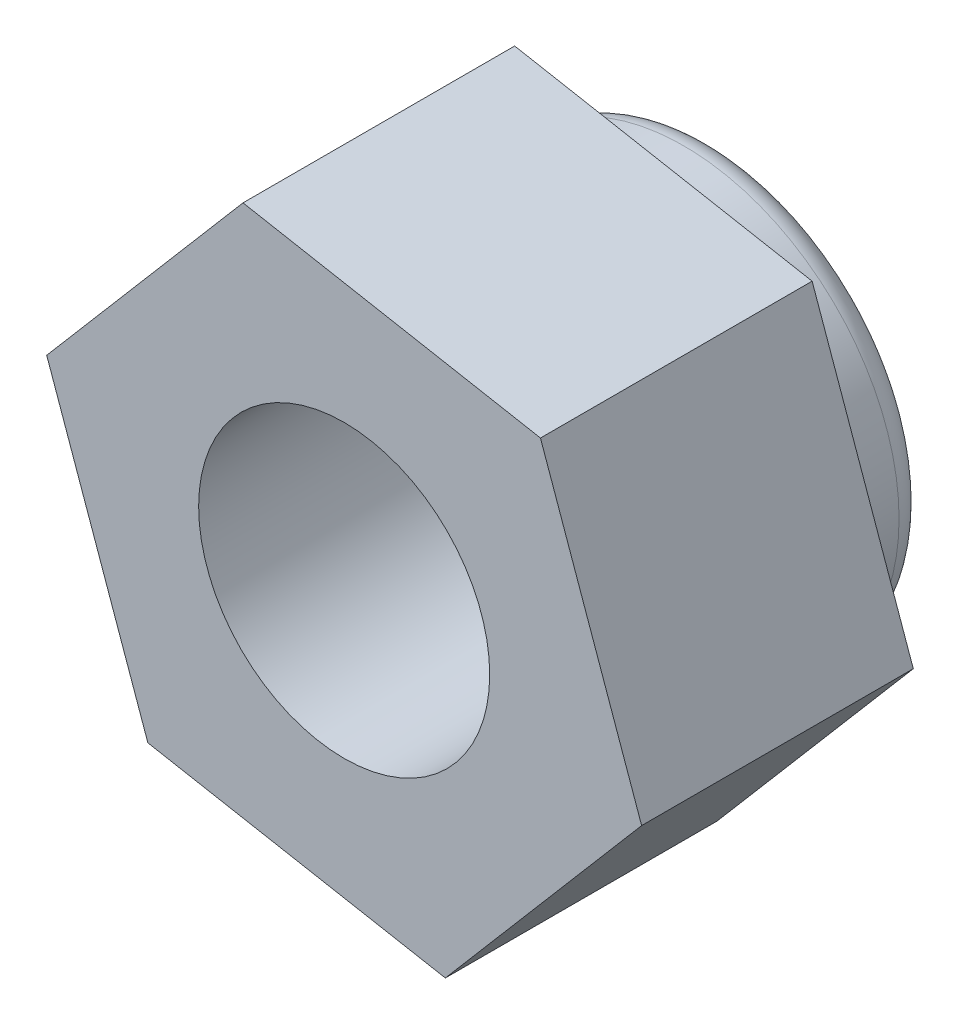
SolidWorks part; units mm, degrees
ref_plane "前视基准面" through (0, 0, 0) normal (0, 0, 1) x (1, 0, 0)
ref_plane "上视基准面" through (0, 0, 0) normal (0, 1, 0) x (1, 0, 0)
ref_plane "右视基准面" through (0, 0, 0) normal (1, 0, 0) x (0, 0, -1)
sketch "草图1" plane through (0, 0, 0) normal (0, 0, 1) x (1, 0, 0)
  line L1 (-1.0427, 2.9382) -> (-3.0659, 0.5661)
  line L2 (-3.0659, 0.5661) -> (-2.0232, -2.3721)
  line L3 (-2.0232, -2.3721) -> (1.0427, -2.9382)
  line L4 (1.0427, -2.9382) -> (3.0659, -0.5661)
  line L5 (3.0659, -0.5661) -> (2.0232, 2.3721)
  line L6 (2.0232, 2.3721) -> (-1.0427, 2.9382)
  circle A0 centre (0, 0) radius 1.5
  circle A1 centre (0, 0) radius 2.7 construction
  dimension "D1" = 1.5
  dimension "D2" = 5.4
extrude "凸台-拉伸1" add sketch "草图1" along normal blind 3.8
cosmetic thread "装饰螺纹线1" parameters "D2"=9
sketch "草图2" plane through (0, 0, 0) normal (0, 0, -1) x (-1, 0, 0)
  circle A0 centre (0, 0) radius 2.2192
  dimension "D1" = 2.2192
extrude "切除-拉伸1" cut sketch "草图2" against normal blind 1 flip side to cut
fillet "圆角1" radius 0.3 1 edges at (-2.2192, 0, 0)
